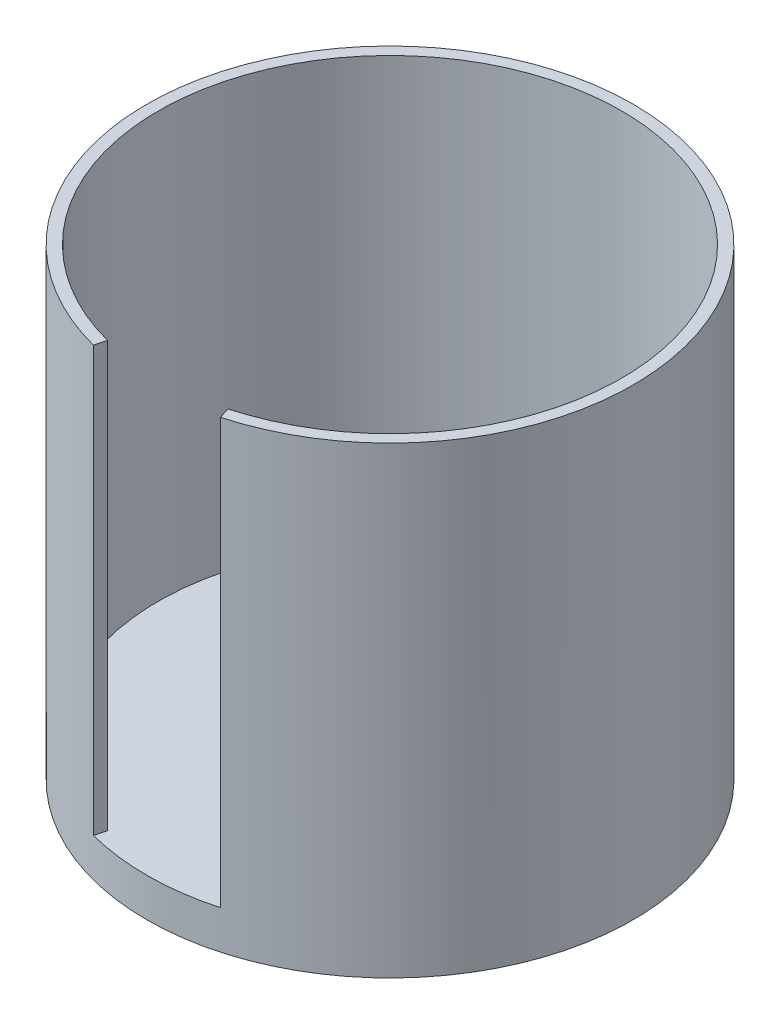
SolidWorks part; units mm, degrees
ref_plane "Plan de face" through (0, 0, 0) normal (0, 0, 1) x (1, 0, 0)
ref_plane "Plan de dessus" through (0, 0, 0) normal (0, 1, 0) x (1, 0, 0)
ref_plane "Plan de droite" through (0, 0, 0) normal (1, 0, 0) x (0, 0, -1)
sketch "Esquisse1" plane through (0, 0, 0) normal (0, 0, 1) x (1, 0, 0)
  line L0 (0, 0) -> (0, 60)
  line L1 (0, 60) -> (31.5, 60)
  line L2 (31.5, 60) -> (31.5, 0)
  line L3 (31.5, 0) -> (0, 0)
  dimension "D1" = 60
  dimension "D2" = 31.5
revolve "Révolution1" add sketch "Esquisse1" angle 360 about L0
sketch "Esquisse2" plane through (0, 60, 0) normal (0, 1, 0) x (1, 0, 0)
  line L0 (-7.9238, -30.4871) -> (0, 0)
  line L1 (0, 0) -> (8.3813, -30.3645)
  circle A0 centre (0, 0) radius 30
  circle A1 centre (0, 0) radius 31.5 construction
  arc A2 (-7.9238, -30.4871) -> (8.3813, -30.3645) centre (0, 0) ccw
  dimension "D1" = 60
extrude "Enlèv. mat.-Extru.4" cut sketch "Esquisse2" against normal blind 55 contours L0 A0 L1 | L1 A0 L0
sketch "Esquisse4" plane through (0, 0, 0) normal (0, -1, 0) x (-1, 0, 0)
  line L0 (-1, -1.118) -> (-1, 1.118)
  line L1 (0, 0) -> (-1, 0) construction
  line L2 (-1, 0) -> (1.5, 0) construction
  circle A0 centre (0, 0) radius 1.5
  dimension "D1" = 3
  dimension "D2" = 2.5
extrude "Enlèv. mat.-Extru.7" cut sketch "Esquisse4" against normal blind 4 contours L0 A0
sketch "Esquisse6" plane through (0, 0, 0) normal (0, 0, 1) x (1, 0, 0)
  line L0 (0, 0) -> (0, 143.4014) construction
